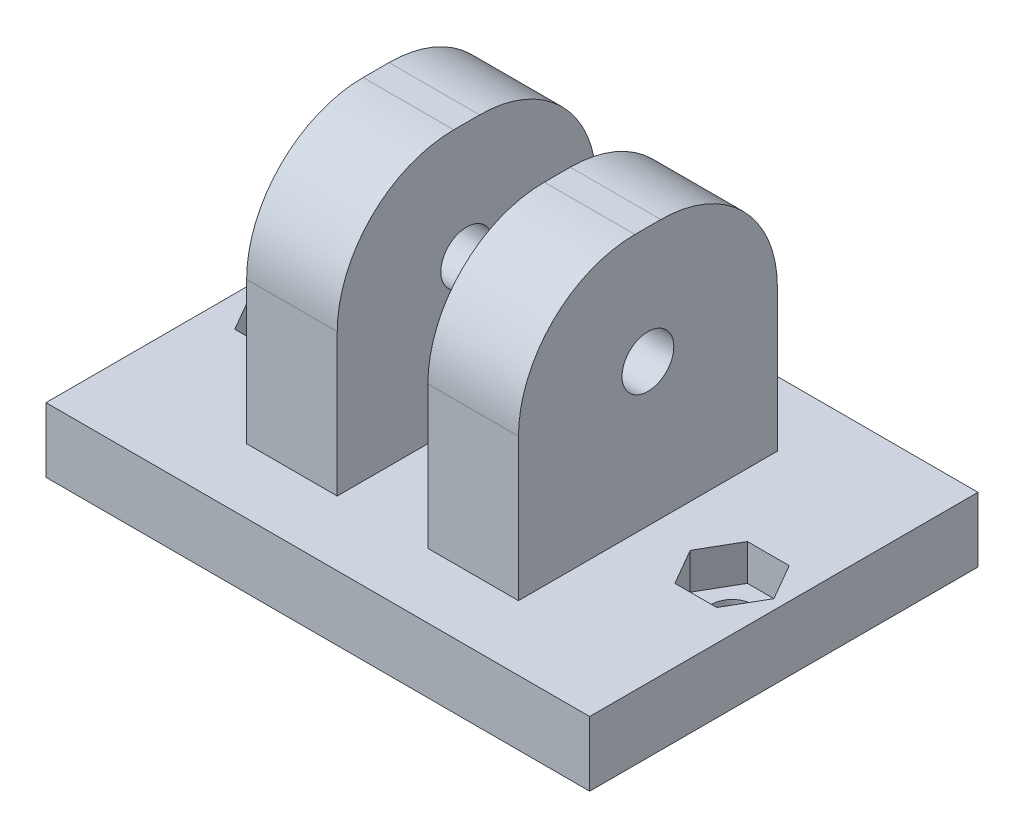
SolidWorks part; units mm, degrees
ref_plane "Alzado" through (0, 0, 0) normal (0, 0, 1) x (1, 0, 0)
ref_plane "Planta" through (0, 0, 0) normal (0, 1, 0) x (1, 0, 0)
ref_plane "Vista lateral" through (0, 0, 0) normal (1, 0, 0) x (0, 0, -1)
sketch "Croquis1" plane through (0, 0, 0) normal (0, 0, 1) x (1, 0, 0)
  line L1 (-21, 0) -> (21, 0)
  line L2 (-21, 0) -> (-21, 5)
  line L3 (-21, 5) -> (21, 5)
  line L4 (21, 0) -> (21, 5)
  point P4 (0, 0)
  dimension "D1" = 5
  dimension "D2" = 42
extrude "Saliente-Extruir1" add sketch "Croquis1" along normal blind 30
sketch "Croquis2" plane through (0, 5, 0) normal (0, 1, 0) x (1, 0, 0)
  line L0 (-21, -15) -> (-13, -15) construction
  line L1 (-21, -30) -> (-21, 0) construction
  line L2 (0, 0) -> (0, -30) construction
  line L3 (21, -30) -> (-21, -30) construction
  circle A0 centre (-17, -15) radius 1.6
  circle A1 centre (17, -15) radius 1.6
  dimension "D2" = 3.2
  dimension "D1" = 8
extrude "Cortar-Extruir1" cut sketch "Croquis2" against normal blind 21 and the other way blind 15
sketch "Croquis3" plane through (0, 5, 0) normal (0, 1, 0) x (1, 0, 0)
  line L0 (0, 0) -> (0, -30) construction
  line L1 (21, 0) -> (-21, 0) construction
  line L2 (21, -30) -> (-21, -30) construction
  line L3 (15.3834, -17.8) -> (13.7668, -15)
  line L4 (-13.7668, -15) -> (-15.3834, -12.2)
  line L5 (-15.3834, -12.2) -> (-18.6166, -12.2)
  line L6 (-18.6166, -12.2) -> (-20.2332, -15)
  line L7 (-20.2332, -15) -> (-18.6166, -17.8)
  line L8 (-18.6166, -17.8) -> (-15.3834, -17.8)
  line L9 (-15.3834, -17.8) -> (-13.7668, -15)
  line L10 (18.6166, -17.8) -> (15.3834, -17.8)
  line L11 (20.2332, -15) -> (18.6166, -17.8)
  line L12 (18.6166, -12.2) -> (20.2332, -15)
  line L13 (15.3834, -12.2) -> (18.6166, -12.2)
  line L14 (13.7668, -15) -> (15.3834, -12.2)
  circle A0 centre (-17, -15) radius 2.8 construction
  dimension "D1" = 5.6
extrude "Cortar-Extruir2" cut sketch "Croquis3" against normal blind 2.8
sketch "Croquis4" plane through (0, 5, 0) normal (0, 1, 0) x (1, 0, 0)
  line L0 (0, 0) -> (0, -30) construction
  line L1 (-10.5, -25) -> (-3.5, -25)
  line L2 (-10.5, -25) -> (-10.5, -5)
  line L3 (-10.5, -5) -> (-3.5, -5)
  line L4 (10.5, -25) -> (10.5, -5)
  line L5 (-10.5, -25) -> (-3.5, -18.3333) construction
  line L6 (-10.5, -5) -> (-3.5, -11.6667) construction
  line L7 (21, 0) -> (-21, 0) construction
  line L8 (21, -30) -> (-21, -30) construction
  line L9 (3.5, -5) -> (10.5, -5)
  line L11 (-3.5, -25) -> (-3.5, -5)
  line L13 (3.5, -25) -> (3.5, -5)
  line L14 (3.5, -18.3333) -> (10.5, -25) construction
  line L15 (3.5, -11.6667) -> (10.5, -5) construction
  line L16 (3.5, -25) -> (10.5, -25)
  point P0 (0, -15)
  point P12 (0, -15)
  dimension "D1" = 21
  dimension "D2" = 20
  dimension "D3" = 7
extrude "Saliente-Extruir2" add sketch "Croquis4" along normal blind 20
fillet "Redondeo1" radius 9 4 edges at (7, 25, 25) (7, 25, 5) (-7, 25, 5) (-7, 25, 25)
sketch "Croquis5" plane through (10.5, 0, 0) normal (1, 0, 0) x (0, 0, -1)
  line L0 (-25, 16) -> (-5, 16) construction
  circle A0 centre (-15, 16) radius 2
  dimension "D1" = 4
extrude "Cortar-Extruir3" cut sketch "Croquis5" against normal blind 23 and the other way blind 11
